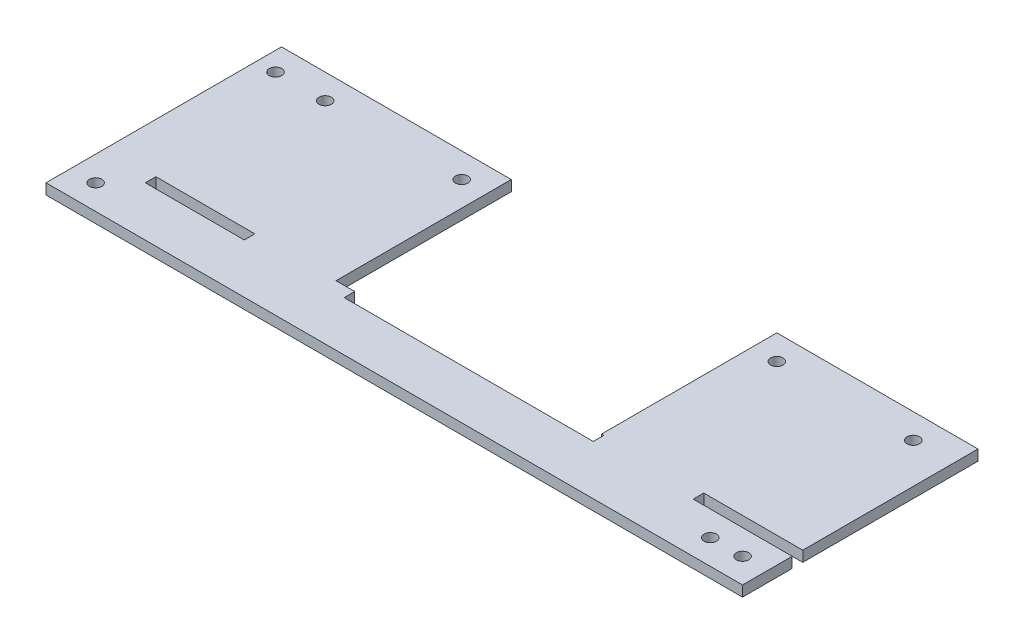
SolidWorks part; units mm, degrees
ref_plane "Front Plane" through (0, 0, 0) normal (0, 0, 1) x (1, 0, 0)
ref_plane "Top Plane" through (0, 0, 0) normal (0, 1, 0) x (1, 0, 0)
ref_plane "Right Plane" through (0, 0, 0) normal (1, 0, 0) x (0, 0, -1)
sketch "Sketch1" plane through (0, 0, 0) normal (0, 1, 0) x (1, 0, 0)
  line L0 (-91.8337, -47.6885) -> (-86.7283, -47.6885) construction
  line L1 (-165.481, -47.5361) -> (165.481, -47.5361)
  line L2 (-165.481, -47.5361) -> (-165.481, 47.5361)
  line L3 (-165.481, 47.5361) -> (165.481, 47.5361)
  line L4 (165.481, -47.5361) -> (165.481, 47.5361)
  line L5 (-165.481, -47.5361) -> (165.481, 47.5361) construction
  line L6 (-165.481, 47.5361) -> (165.481, -47.5361) construction
  line L7 (-165.481, -47.5361) -> (-114.8334, -47.5361)
  line L8 (-165.481, -47.5361) -> (-165.481, -42.1259)
  line L9 (-165.481, -42.1259) -> (-114.8334, -42.1259)
  line L10 (-114.8334, -47.5361) -> (-114.8334, -42.1259)
  line L11 (-63.7286, -47.5361) -> (63.7286, -47.5361)
  line L12 (-63.7286, -47.5361) -> (-63.7286, -42.1259)
  line L13 (-63.7286, -42.1259) -> (63.7286, -42.1259)
  line L14 (63.7286, -47.5361) -> (63.7286, -42.1259)
  line L15 (165.481, -47.5361) -> (114.8334, -47.5361)
  line L16 (165.481, -47.5361) -> (165.481, -42.1259)
  line L17 (165.481, -42.1259) -> (114.8334, -42.1259)
  line L18 (114.8334, -47.5361) -> (114.8334, -42.1259)
  line L19 (-165.481, 47.5361) -> (-190.881, 47.5361)
  line L20 (-165.481, 47.5361) -> (-165.481, -47.5361)
  line L21 (-165.481, -47.5361) -> (-190.881, -47.5361)
  line L22 (-190.881, 47.5361) -> (-190.881, -47.5361)
  line L23 (-190.881, -47.5361) -> (165.481, -47.5361)
  line L24 (-190.881, -47.5361) -> (-190.881, -72.9361)
  line L25 (-190.881, -72.9361) -> (165.481, -72.9361)
  line L26 (165.481, -47.5361) -> (165.481, -72.9361)
  line L27 (-91.9861, -47.5361) -> (-86.5759, -47.5361)
  line L28 (-91.9861, -47.5361) -> (-91.9861, -60.2361)
  line L29 (-91.9861, -60.2361) -> (-86.5759, -60.2361)
  line L30 (-86.5759, -47.5361) -> (-86.5759, -60.2361)
  line L31 (-86.7283, -47.6885) -> (-86.7283, -60.0837) construction
  line L32 (-91.8337, -60.0837) -> (-86.7283, -60.0837) construction
  line L33 (-91.8337, -47.6885) -> (-91.8337, -60.0837) construction
  line L34 (86.7283, -47.6885) -> (91.8337, -47.6885) construction
  line L35 (86.5759, -47.5361) -> (91.9861, -47.5361)
  line L36 (86.5759, -47.5361) -> (86.5759, -60.2361)
  line L37 (86.5759, -60.2361) -> (91.9861, -60.2361)
  line L38 (91.9861, -47.5361) -> (91.9861, -60.2361)
  line L39 (91.8337, -47.6885) -> (91.8337, -60.0837) construction
  line L40 (86.7283, -60.0837) -> (91.8337, -60.0837) construction
  line L41 (86.7283, -47.6885) -> (86.7283, -60.0837) construction
  line L42 (-73.3069, 47.5361) -> (-73.3069, -42.1259)
  line L43 (-73.3069, -42.1259) -> (62.5475, -42.1259)
  line L44 (62.5475, -42.1259) -> (62.5475, 47.5361)
  circle A0 centre (-155.829, 34.8361) radius 3.175
  circle A1 centre (-86.0069, 34.8361) radius 3.175
  circle A2 centre (75.2475, 34.8361) radius 3.175
  circle A3 centre (145.0696, 34.8361) radius 3.175
  circle A4 centre (-181.229, 34.8361) radius 3.175
  circle A5 centre (-178.181, -60.2361) radius 3.175
  circle A6 centre (152.781, -60.2361) radius 3.175
  circle A9 centre (136.271, -60.2361) radius 3.175
  point P0 (0, 0)
  dimension "D10" = 69.8221
  dimension "D18" = 25.4
  dimension "D22" = 6.35
  dimension "D23" = 12.7
  dimension "D25" = 12.7
  dimension "D27" = 12.7
  dimension "D28" = 12.7
  dimension "D39" = 29.21
  dimension "D1" = 330.962
  dimension "D2" = 95.0722
  dimension "D3" = 50.6476
  dimension "D4" = 5.4102
  dimension "D5" = 50.6476
  dimension "D6" = 5.4102
  dimension "D7" = 51.1048
  dimension "D8" = 51.1048
  dimension "D9" = 5.4102
  dimension "D11" = 9.652
  dimension "D12" = 240.7285
  dimension "D13" = 69.8221
  dimension "D14" = 12.7
  dimension "D15" = 12.7
  dimension "D16" = 12.7
  dimension "D17" = 12.7
  dimension "D19" = 25.4
  dimension "D20" = 12.7
  dimension "D21" = 25.4
  dimension "D24" = 12.7
  dimension "D26" = 12.7
  dimension "D30" = 5.4102
  dimension "D31" = 12.7
  dimension "D32" = 22.8473
  dimension "D33" = 22.8473
  dimension "D35" = 12.7
  dimension "D36" = 5.4102
  dimension "D37" = 22.8473
  dimension "D34" = 0.1524
  dimension "D38" = 0.1524
extrude "Boss-Extrude1" add sketch "Sketch1" along normal blind 5.4102 contours L43 L42 L3 L2 L9 L10 L1 L23 L12 A1 A0 | L1 L38 L37 L36 L30 L29 L28 L21 L24 L25 L26 A9 A6 A5 | L38 L23 L36 L37 | L44 L13 L14 L1 L23 L18 L17 L4 L3 A3 A2 | L19 L22 L21 L2 A4
